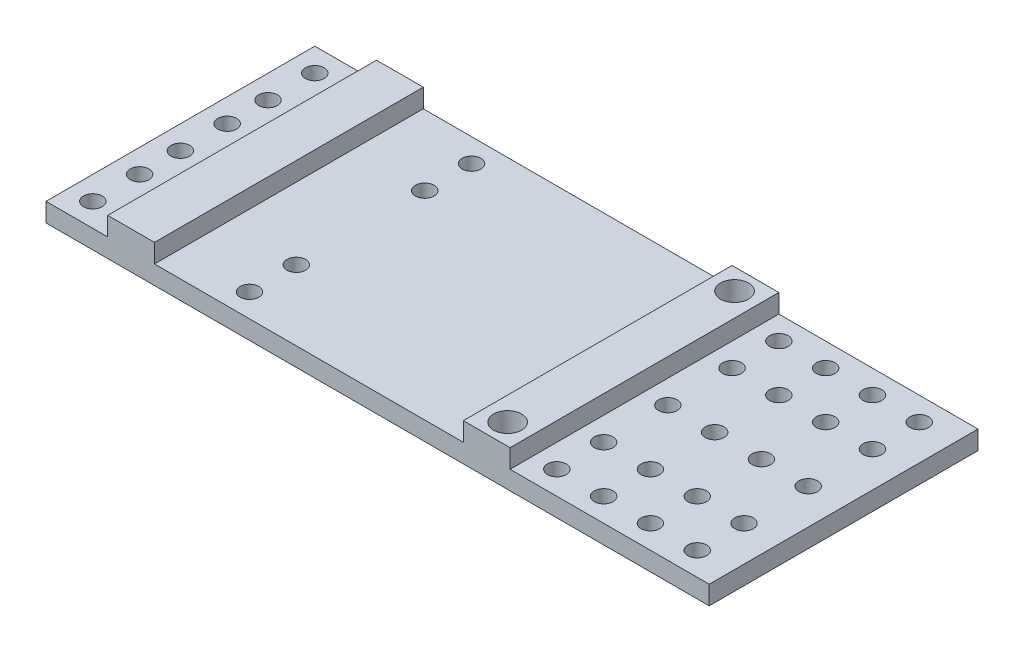
SolidWorks part; units mm, degrees
ref_plane "Front Plane" through (0, 0, 0) normal (0, 0, 1) x (1, 0, 0)
ref_plane "Top Plane" through (0, 0, 0) normal (0, 1, 0) x (1, 0, 0)
ref_plane "Right Plane" through (0, 0, 0) normal (1, 0, 0) x (0, 0, -1)
sketch "Sketch1" plane through (0, 0, 0) normal (0, 1, 0) x (1, 0, 0)
  line L0 (-107.1442, -9.0484) -> (110.6392, -9.0484) construction
  line L1 (-107.1442, 19.6766) -> (34.6058, 19.6766)
  line L2 (-107.1442, 19.6766) -> (-107.1442, -37.7734)
  line L3 (-107.1442, -37.7734) -> (34.6058, -37.7734)
  line L4 (34.6058, 19.6766) -> (34.6058, -37.7734)
  circle A0 centre (-102.1442, 14.6766) radius 2
  circle A1 centre (-68.6442, 14.6766) radius 2
  circle A2 centre (-68.6442, 4.6766) radius 2
  circle A3 centre (-102.1442, 4.6766) radius 2
  circle A4 centre (-102.1442, -22.7734) radius 2
  circle A5 centre (-68.6442, -32.7734) radius 2
  circle A6 centre (-68.6442, -22.7734) radius 2
  circle A7 centre (-102.1442, -32.7734) radius 2
  dimension "D7" = 4
  dimension "D1" = 57.45
  dimension "D2" = 141.75
  dimension "D3" = 5
  dimension "D4" = 5
  dimension "D5" = 2
  dimension "D6" = 2
extrude "Plate2BAse" add sketch "Sketch1" along normal blind 4
sketch "Sketch2" plane through (0, 4, 0) normal (0, 1, 0) x (1, 0, 0)
  line L0 (34.6058, 19.6766) -> (-107.1442, 19.6766) construction
  line L1 (-93.956, 19.6766) -> (-7.956, 19.6766)
  line L2 (-93.956, 19.6766) -> (-93.956, -37.7734)
  line L3 (-93.956, -37.7734) -> (-7.956, -37.7734)
  line L4 (-7.956, 19.6766) -> (-7.956, -37.7734)
  line L5 (-107.1442, -37.7734) -> (34.6058, -37.7734) construction
  dimension "D1" = 86
sketch "Sketch3" plane through (0, 4, 0) normal (0, 1, 0) x (1, 0, 0)
  line L0 (-93.956, -37.7734) -> (-7.956, -37.7734) construction
  line L1 (-93.956, 19.6766) -> (-83.956, 19.6766)
  line L2 (-93.956, 19.6766) -> (-93.956, -37.7734)
  line L3 (-93.956, -37.7734) -> (-83.956, -37.7734)
  line L4 (-83.956, 19.6766) -> (-83.956, -37.7734)
  line L6 (-7.956, 19.6766) -> (-17.956, 19.6766)
  line L7 (-7.956, 19.6766) -> (-7.956, -37.7734)
  line L8 (-7.956, -37.7734) -> (-17.956, -37.7734)
  line L9 (-17.956, 19.6766) -> (-17.956, -37.7734)
  dimension "D1" = 10
  dimension "D2" = 10
extrude "PiBase" add sketch "Sketch3" along normal blind 4
sketch "Sketch4" plane through (0, 8, 0) normal (0, 1, 0) x (1, 0, 0)
  line L0 (-7.956, -9.0484) -> (-113.7907, -9.0484) construction
  line L1 (-7.956, 19.6766) -> (-7.956, -37.7734) construction
  line L2 (-17.956, 19.6766) -> (-7.956, 19.6766) construction
  line L3 (-7.956, 19.6766) -> (-12.956, 19.6766) construction
  line L4 (-12.956, 19.6766) -> (-12.956, -53.6344) construction
  circle A0 centre (-12.956, 15.2016) radius 3
  circle A1 centre (-12.956, -33.2984) radius 3
  dimension "D1" = 24.25
extrude "PiMount" cut sketch "Sketch4" against normal blind 22
sketch "Sketch5" plane through (0, 4, 0) normal (0, 1, 0) x (1, 0, 0)
  line L0 (34.6058, 19.6766) -> (-7.956, 19.6766) construction
  line L1 (-7.956, 19.6766) -> (-7.956, -37.7734) construction
  line L2 (34.6058, -9.0484) -> (-26.4491, -9.0484) construction
  line L3 (34.6058, -37.7734) -> (34.6058, 19.6766) construction
  circle A0 centre (-2.956, 14.6766) radius 2
  circle A16 centre (7.044, 14.6766) radius 2
  circle A17 centre (17.044, 14.6766) radius 2
  circle A18 centre (27.044, 14.6766) radius 2
  circle A19 centre (7.044, 4.6766) radius 2
  circle A20 centre (17.044, 4.6766) radius 2
  circle A21 centre (27.044, 4.6766) radius 2
  circle A22 centre (-2.956, 4.6766) radius 2
  circle A23 centre (-2.956, -22.7734) radius 2
  circle A24 centre (27.044, -22.7734) radius 2
  circle A25 centre (17.044, -22.7734) radius 2
  circle A26 centre (7.044, -22.7734) radius 2
  circle A27 centre (27.044, -32.7734) radius 2
  circle A28 centre (17.044, -32.7734) radius 2
  circle A29 centre (7.044, -32.7734) radius 2
  circle A30 centre (-2.956, -32.7734) radius 2
  circle A31 centre (-2.956, -9.0484) radius 2
  circle A32 centre (7.044, -9.0484) radius 2
  circle A33 centre (17.044, -9.0484) radius 2
  circle A34 centre (27.044, -9.0484) radius 2
  dimension "D1" = 5
  dimension "D5" = 4
  dimension "D2" = 5
  dimension "D3" = 4
  dimension "D4" = 2
extrude "Cut-Extrude2" cut sketch "Sketch5" against normal blind 4
sketch "Sketch6" plane through (0, 4, 0) normal (0, 1, 0) x (1, 0, 0)
  line L0 (-107.1442, -9.0484) -> (-73.6322, -9.0484) construction
  line L1 (-107.1442, 19.6766) -> (-107.1442, -37.7734) construction
  line L2 (-102.1442, 4.6766) -> (-102.1442, -23.7881) construction
  circle A0 centre (-102.1442, -4.0484) radius 2
  circle A1 centre (-102.1442, -14.0484) radius 2
  dimension "D1" = 5
extrude "CamMount" cut sketch "Sketch6" against normal blind 4
